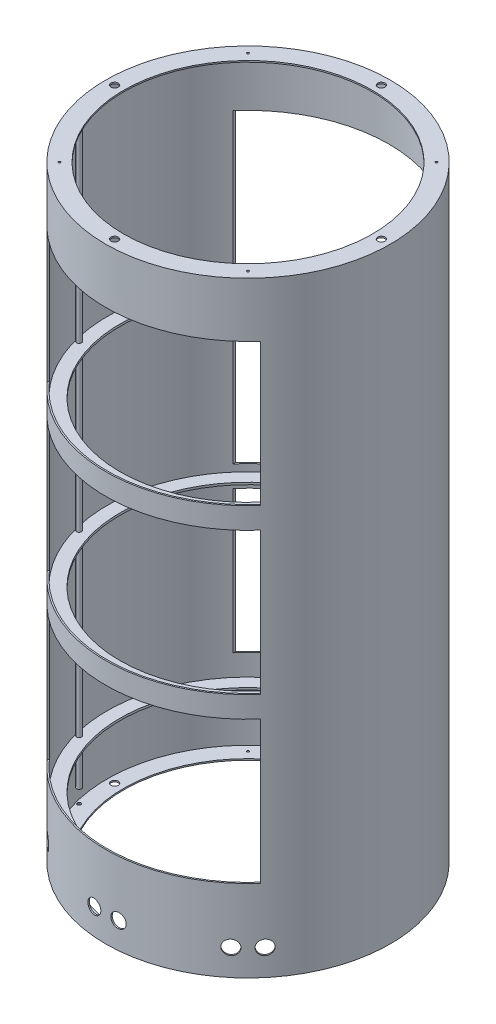
SolidWorks part; units mm, degrees
material "6061 Alloy"
ref_plane "Front Plane" through (0, 0, 0) normal (0, 0, 1) x (1, 0, 0)
ref_plane "Top Plane" through (0, 0, 0) normal (0, 1, 0) x (1, 0, 0)
ref_plane "Right Plane" through (0, 0, 0) normal (1, 0, 0) x (0, 0, -1)
sketch "Sketch1" plane through (0, 0, 0) normal (0, 1, 0) x (1, 0, 0)
  circle A0 centre (0, 0) radius 200
  dimension "D1" = 400
extrude "Boss-Extrude1" add sketch "Sketch1" along normal blind 1000
sketch "Sketch2" plane through (0, 0, 0) normal (0, 0, 1) x (1, 0, 0)
  line L0 (-214.7996, -4.3814) -> (185.2004, -4.3814) construction
  dimension "D1" = 400
shell "Shell1" thickness 2
sketch "Sketch3" plane through (0, 0, 0) normal (0, 0, 1) x (1, 0, 0)
  line L0 (-198, 998) -> (198, 998) construction
  line L1 (-150, 463) -> (150, 463)
  line L2 (-150, 463) -> (-150, 263)
  line L3 (-150, 263) -> (150, 263)
  line L4 (150, 463) -> (150, 263)
  line L5 (-150, 693) -> (150, 693)
  line L6 (-150, 693) -> (-150, 493)
  line L7 (-150, 493) -> (150, 493)
  line L8 (150, 693) -> (150, 493)
  line L9 (-150, 923) -> (150, 923)
  line L10 (-150, 923) -> (-150, 723)
  line L11 (-150, 723) -> (150, 723)
  line L12 (150, 923) -> (150, 723)
  point P12 (0, 263)
  dimension "D1" = 75
  dimension "D2" = 200
  dimension "D3" = 30
  dimension "D4" = 200
  dimension "D5" = 200
  dimension "D6" = 30
  dimension "D7" = 300
  dimension "D8" = 300
  dimension "D9" = 300
extrude "Cut-Extrude2" cut sketch "Sketch3" against normal mid plane 1000
ref_plane "Plane1" through (0, 693, 0) normal (0, -1, 0) x (-1, 0, 0)
ref_plane "Plane2" through (0, 263, 0) normal (0, 1, 0) x (1, 0, 0)
ref_plane "Plane3" through (0, 1000, 0) normal (0, 1, 0) x (1, 0, 0)
sketch "Sketch15" plane through (0, 1000, 0) normal (0, 1, 0) x (1, 0, 0)
  circle A0 centre (0, 0) radius 175
  dimension "D1" = 350
extrude "Cut-Extrude8" cut sketch "Sketch15" against normal up to next
sketch "Sketch18" plane through (0, 0, 0) normal (0, 0, 1) x (1, 0, 0)
  line L0 (-200, 0) -> (200, 0) construction
  line L1 (-210, 150) -> (210, 150)
  line L2 (-210, 150) -> (-210, -10)
  line L3 (-210, -10) -> (210, -10)
  line L4 (210, 150) -> (210, -10)
  line L5 (200, 0) -> (200, 1000) construction
  dimension "D1" = 10
  dimension "D2" = 160
  dimension "D3" = 10
  dimension "D4" = 420
extrude "Cut-Extrude11" cut sketch "Sketch18" against normal blind 350 and the other way blind 250
sketch "Sketch19" plane through (0, 150, 0) normal (0, -1, 0) x (1, 0, 0)
  circle A0 centre (0, 0) radius 200 construction
  circle A1 centre (0, 0) radius 200 construction
  circle A2 centre (0, 0) radius 175
  circle A3 centre (0, 0) radius 200
  dimension "D1" = 350
extrude "Boss-Extrude3" add sketch "Sketch19" along normal blind 2
sketch "Sketch16" plane through (0, 1000, 0) normal (0, 1, 0) x (1, 0, 0)
  circle A0 centre (0, 187.5) radius 5.1
  circle A1 centre (187.5, 0) radius 5.1
  circle A2 centre (0, -187.5) radius 5.1
  circle A3 centre (-187.5, 0) radius 5.1
  dimension "D3" = 10.2
  dimension "D1" = 187.5
  dimension "D2" = 4
extrude "Cut-Extrude9" cut sketch "Sketch16" against normal blind 910
sketch "Sketch17" plane through (0, 1000, 0) normal (0, 1, 0) x (1, 0, 0)
  line L0 (0, 200) -> (0, 0) construction
  line L1 (-132.5825, 132.5825) -> (0, 0) construction
  circle A0 centre (-132.5825, 132.5825) radius 1.5
  circle A1 centre (0, 0) radius 200 construction
  circle A2 centre (132.5825, 132.5825) radius 1.5
  circle A3 centre (132.5825, -132.5825) radius 1.5
  circle A4 centre (-132.5825, -132.5825) radius 1.5
  circle A5 centre (0, 187.5) radius 5.1 construction
  dimension "D1" = 3
  dimension "D2" = 187.5
  dimension "D3" = 45
  dimension "D5" = 132.5825
  dimension "D4" = 4
extrude "Cut-Extrude10" cut sketch "Sketch17" against normal through all
sketch "Sketch21" plane through (0, 693, 0) normal (0, -1, 0) x (-1, 0, 0)
  circle A0 centre (0, 0) radius 198 construction
  circle A1 centre (0, 0) radius 198
  circle A2 centre (0, 0) radius 180
  dimension "D1" = 360
extrude "Boss-Extrude4" add sketch "Sketch21" along normal blind 3 from offset 20 offset against normal yes
pattern_linear "LPattern1" count 2 spacing 230 along (0, -1, 0) of "Boss-Extrude4"
pattern_linear "LPattern2" count 2 spacing 480 along (0, -1, 0) of "Boss-Extrude4"
sketch "Sketch23" plane through (0, 150, 0) normal (0, 1, 0) x (1, 0, 0)
  circle A0 centre (-187.446, -50) radius 2.5
  circle A1 centre (-187.446, -50) radius 3.5
  circle A2 centre (-187.5, 0) radius 5.1 construction
  circle A3 centre (0, 0) radius 175 construction
  dimension "D1" = 5
  dimension "D2" = 7
  dimension "D3" = 50
  dimension "D4" = 194
extrude "Boss-Extrude5" add sketch "Sketch23" along normal blind 800 from offset 20
sketch "Sketch24" plane through (0, 713, 0) normal (0, 1, 0) x (1, 0, 0)
  circle A1 centre (-187.446, -50) radius 2.5
  circle A2 centre (-187.446, -50) radius 2.5
  dimension "D1" = 0
extrude "Cut-Extrude12" cut sketch "Sketch24" against normal through all
sketch "Sketch26" plane through (-142.8356, 0, 142.8356) normal (-0.7071, 0, 0.7071) x (0.7071, 0, 0.7071)
  circle A0 centre (17, 184.8) radius 9 construction
  circle A1 centre (-17, 184.8) radius 9
  circle A2 centre (-17, 184.8) radius 9 construction
  circle A3 centre (17, 184.8) radius 9 construction
  circle A4 centre (-17, 184.8) radius 10
  circle A5 centre (17, 184.8) radius 10
  dimension "D2" = 1
  dimension "D3" = 1
  dimension "D1" = 0
sketch "Sketch28" plane through (0, 0, 202) normal (0, 0, 1) x (1, 0, 0)
  circle A0 centre (17, 184.8) radius 9 construction
  circle A1 centre (-17, 184.8) radius 9 construction
  circle A2 centre (17, 184.8) radius 9 construction
  circle A3 centre (-17, 184.8) radius 9 construction
  circle A4 centre (-17, 184.8) radius 10
  circle A5 centre (17, 184.8) radius 10
  dimension "D1" = 1
  dimension "D2" = 1
sketch "Sketch29" plane through (142.8356, 0, 142.8356) normal (0.7071, 0, 0.7071) x (0.7071, 0, -0.7071)
  circle A0 centre (17, 184.8) radius 9 construction
  circle A1 centre (-17, 184.8) radius 9 construction
  circle A2 centre (17, 184.8) radius 9 construction
  circle A3 centre (-17, 184.8) radius 9 construction
  circle A4 centre (-17, 184.8) radius 10
  circle A5 centre (17, 184.8) radius 10
  dimension "D1" = 1
  dimension "D2" = 1
extrude "Cut-Extrude13" cut sketch "Sketch26" against normal up to next
extrude "Cut-Extrude14" cut sketch "Sketch28" against normal up to next
extrude "Cut-Extrude15" cut sketch "Sketch29" against normal blind 10
